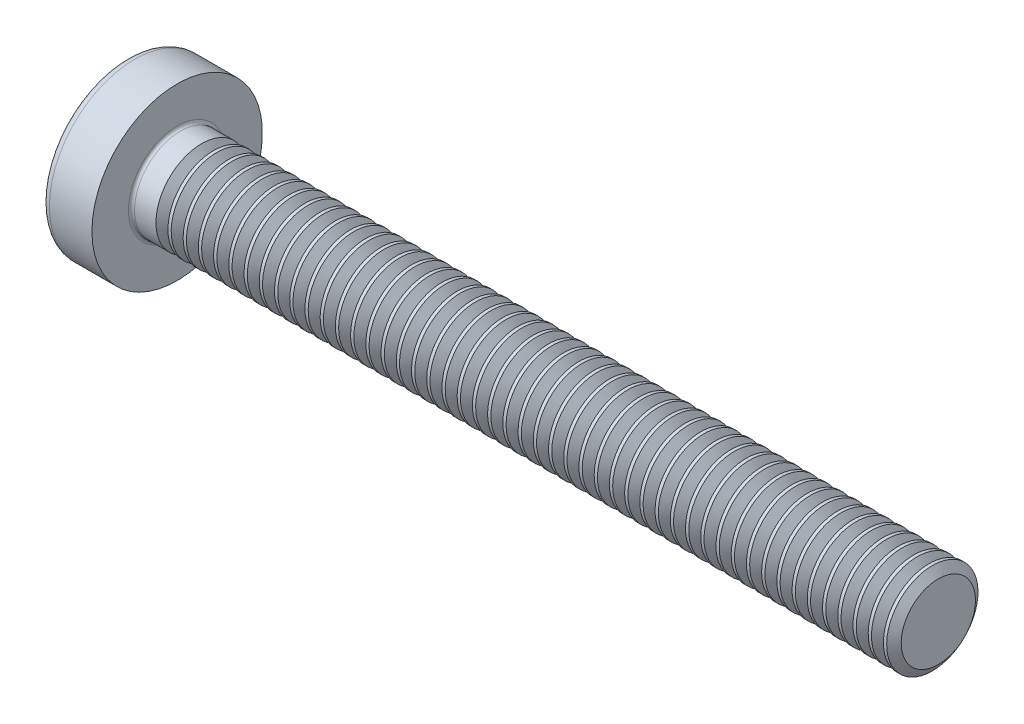
SolidWorks part; units mm, degrees
ref_plane "Plane1" through (0, 0, 0) normal (0, 0, 1) x (1, 0, 0)
ref_plane "Plane2" through (0, 0, 0) normal (0, 1, 0) x (1, 0, 0)
ref_plane "Plane3" through (0, 0, 0) normal (1, 0, 0) x (0, 0, -1)
sketch "BodySke" plane through (0, 0, 0) normal (0, 0, 1) x (1, 0, 0)
  line L0 (2.4, 1.5) -> (2.4, 2.8)
  line L1 (2.65, 6.35) -> (2.65, -3.175) construction
  line L2 (-25.4, 0) -> (127, 0) construction
  line L3 (27.4, 0) -> (0, 0)
  line L4 (2.4, 1.5) -> (27.4, 1.5)
  line L5 (27.4, 1.5) -> (27.4, 0)
  line L6 (1.0035, 2.8) -> (2.4, 2.8)
  line L8 (2.4, 6.35) -> (2.4, -3.175) construction
  arc A0 (0.7754, 2.6744) -> (0, 0) centre (5, 0) ccw
  arc A2 (0.7754, 2.6744) -> (1.0035, 2.8) centre (1.0035, 2.53) cw
  dimension "Head_crown_rad" = 5
  dimension "Head_fillet_rad" = 0.27
  dimension "Length" = 25
  dimension "Head_ht" = 2.4
  dimension "Head_dia" = 5.6
  dimension "Advance" = 0.5
  dimension "Thread_nom" = 25
  dimension "Diameter" = 3
revolve "Base-Revolve" add sketch "BodySke"
cosmetic thread "ThreadCosmetic" [suppressed]
fillet "Fillet1" radius 0.1 1 edges at (2.4, 0, 1.5)
sketch "Sketch3" plane through (0, 0, 0) normal (1, 0, 0) x (0, 0, -1)
  line L0 (0.37, -1.4) -> (-0.37, -1.4)
  line L1 (0.37, -1.4) -> (0.37, 1.4)
  line L2 (-0.37, 1.4) -> (0.37, 1.4)
  line L3 (-0.37, 1.4) -> (-0.37, -1.4)
  dimension "Cross_dia" = 2.8
  dimension "D1" = 1.4
  dimension "Cross_width" = 0.74
  dimension "D2" = 0.37
ref_plane "Plane4" through (1.75, 0, 0) normal (1, 0, 0) x (0, 0, -1)
sketch "Sketch4" plane through (1.75, 0, 0) normal (1, 0, 0) x (0, 0, -1)
  line L0 (0.37, -0.5275) -> (-0.37, -0.5275)
  line L1 (0.37, -0.5275) -> (0.37, 0.5275)
  line L2 (-0.37, 0.5275) -> (0.37, 0.5275)
  line L3 (-0.37, 0.5275) -> (-0.37, -0.5275)
  dimension "D1" = 0.74
  dimension "D2" = 1.055
  dimension "D3" = 0.37
  dimension "D4" = 0.5275
loft "Recess" cut profiles "Sketch3", "Sketch4"
pattern_circular "RecPat" count 2 every 90 about axis through (0, 0, 0) along (1, 0, 0) of "Recess"
sketch "RecCorSke" plane through (0, 0, 0) normal (0, 0, 1) x (1, 0, 0)
  line L0 (-3.175, 0) -> (15.875, 0) construction
  line L1 (-25.4, 0) -> (127, 0) construction
  line L2 (0, 0) -> (0, 0.6784)
  line L3 (0, 0.6784) -> (1.75, 0.556)
  line L4 (1.75, 0.556) -> (1.9307, 0)
  line L5 (1.9307, 0) -> (0, 0)
  dimension "Diameter" = 1.112
  dimension "Depth" = 1.75
  dimension "Draft_angle" = 4
  dimension "Bottom_angle" = 18
revolve "RecessCore" cut sketch "RecCorSke" angle 360 about L0
sketch "ThdSchSke" plane through (0, 0, 0) normal (0, 0, 1) x (1, 0, 0)
  line L0 (3.4, -1.2195) -> (3.2036, -1.5)
  line L1 (3.4, -1.2195) -> (3.5964, -1.5)
  line L2 (3.5964, -1.5) -> (3.5964, -1.875)
  line L3 (-3.175, 0) -> (5.1513, 0) construction
  line L5 (3.5964, -1.875) -> (3.2036, -1.875)
  line L6 (3.2036, -1.875) -> (3.2036, -1.5)
  dimension "Diameter" = 3
  dimension "SideAngle" = 55
  dimension "VeeAngle" = 70
  dimension "Thread_minor" = 2.439
  dimension "Overcut" = 3.75
  dimension "Start" = 3.4
revolve "ThreadSchematic" cut sketch "ThdSchSke" angle 360 about L3
pattern_linear "ThdSchPat" count 49 spacing 0.5 along (1, 0, 0) of "ThreadSchematic"
equation "\"D1@Sketch3\" = \"Cross_dia@Sketch3\" / 2"
equation "\"D2@Sketch3\" = \"Cross_width@Sketch3\" / 2"
equation "\"Depth@RecCorSke\" = \"Cross_depth@Plane4\""
equation "\"D1@Sketch4\" = \"Cross_width@Sketch3\""
equation "\"D2@Sketch4\" = \"Cross_dia@Sketch3\" - 2.0 * \"Cross_depth@Plane4\" * tan(26.5  * 0.017453292)"
equation "\"D3@Sketch4\" = \"D1@Sketch4\" / 2"
equation "\"D4@Sketch4\" = \"D2@Sketch4\" / 2"
equation "\"Thread_length@ThreadCosmetic\" = ((sgn( (\"Length@BodySke\" - \"Advance@BodySke\" * 2.0 ) - \"Thread_nom@BodySke\" )-1)*( (\"Length@BodySke\" - \"Advance@BodySke\" * 2.0 ) - \"Thread_nom@BodySke\" ))/-2+ \"Thread_nom@BodySke\""
equation "\"Thread_minor@ThdSchSke\" = \"Thread_minor@ThreadCosmetic\""
equation "\"Diameter@ThdSchSke\" = \"Diameter@BodySke\""
equation "\"Overcut@ThdSchSke\" = \"Diameter@BodySke\" * 1.25"
equation "\"Start@ThdSchSke\" = \"Head_ht@BodySke\" + \"Length@BodySke\" - \"Thread_length@ThreadCosmetic\"  '---Non-countersunk---"
equation "\"Num_threads@ThdSchPat\" = int( \"Thread_length@ThreadCosmetic\" / \"Advance@BodySke\" + 0.999 )  + 1"
equation "\"Advance@ThdSchPat\" = \"Thread_length@ThreadCosmetic\" /  (\"Num_threads@ThdSchPat\" - 1) 'relax it"
